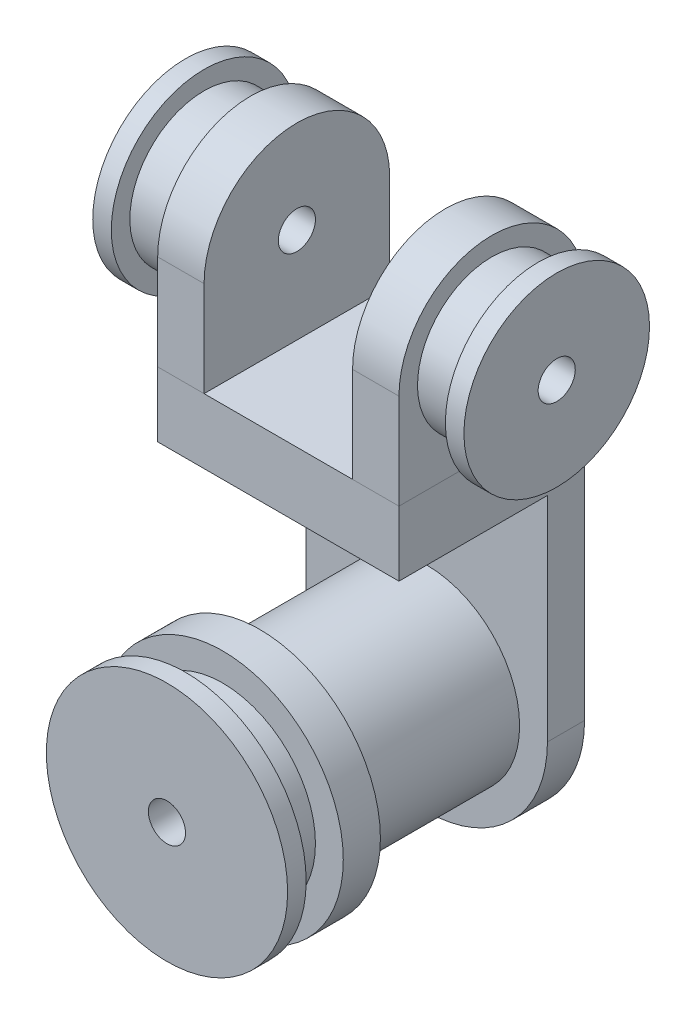
SolidWorks part; units mm, degrees
ref_plane "Front Plane" through (0, 0, 0) normal (0, 0, 1) x (1, 0, 0)
ref_plane "Top Plane" through (0, 0, 0) normal (0, 1, 0) x (1, 0, 0)
ref_plane "Right Plane" through (0, 0, 0) normal (1, 0, 0) x (0, 0, -1)
sketch "Sketch4" plane through (0, 0, 0) normal (0, 0, 1) x (1, 0, 0)
  circle A0 centre (0, 0) radius 1
  circle A1 centre (0, 0) radius 5
  dimension "D1" = 2
  dimension "D2" = 10
extrude "Boss-Extrude5" add sketch "Sketch4" along normal blind 15
ref_plane "Plane2" through (0, 0, 13) normal (0, 0, 1) x (1, 0, 0)
sketch "Sketch5" plane through (0, 0, 15) normal (0, 0, 1) x (1, 0, 0)
  circle A0 centre (0, 0) radius 6.5
  circle A1 centre (0, 0) radius 1 construction
  circle A2 centre (0, 0) radius 1
  dimension "D1" = 13
extrude "Boss-Extrude7" add sketch "Sketch5" against normal blind 2 from surface at -2 starting at plane "Plane2"
sketch "Sketch7" plane through (0, 0, 15) normal (0, 0, 1) x (1, 0, 0)
  circle A0 centre (0, 0) radius 6.5 construction
  circle A1 centre (0, 0) radius 6.5
  circle A2 centre (0, 0) radius 1 construction
  circle A3 centre (0, 0) radius 1
extrude "Boss-Extrude8" add sketch "Sketch7" along normal blind 1
sketch "Sketch8" plane through (0, 0, 0) normal (0, 0, -1) x (-1, 0, 0)
  line L0 (6.5, 0) -> (6.5, 13)
  line L1 (6.5, 13) -> (-6.5, 13)
  line L2 (-6.5, 13) -> (-6.5, 0)
  circle A0 centre (0, 0) radius 6.5 construction
  arc A1 (-6.5, 0) -> (6.5, 0) centre (0, 0) ccw
  circle A2 centre (0, 0) radius 1 construction
  circle A3 centre (0, 0) radius 1
  dimension "D1" = 13
extrude "Boss-Extrude9" add sketch "Sketch8" against normal blind 2
sketch "Sketch9" plane through (0, 0, 0) normal (0, 0, -1) x (-1, 0, 0)
  line L0 (6.5, 0) -> (6.5, 13) construction
  line L3 (-6.5, 13) -> (-6.5, 15)
  line L4 (-6.5, 15) -> (6.5, 15)
  line L5 (6.5, 13) -> (6.5, 15)
  line L6 (-6.5, 13) -> (6.5, 15) construction
  line L7 (-6.5, 15) -> (6.5, 13) construction
  line L8 (-6.5, 13) -> (-6.5, 11.5)
  line L9 (-6.5, 11.5) -> (6.5, 11.5)
  line L10 (6.5, 13) -> (6.5, 11.5)
  line L11 (-6.5, 13) -> (6.5, 11.5) construction
  line L12 (-6.5, 11.5) -> (6.5, 13) construction
  point P5 (0, 14)
  point P8 (0, 12.25)
  dimension "D1" = 2
  dimension "D2" = 1.5
extrude "Boss-Extrude10" add sketch "Sketch9" against normal blind 10
sketch "Sketch10" plane through (6.5, 0, 0) normal (1, 0, 0) x (0, 0, -1)
  line L0 (-5, 20.1326) -> (-5, 15) construction
  line L1 (-10, 15) -> (0, 15) construction
  line L2 (-10, 15) -> (-10, 20.1326)
  line L3 (0, 15) -> (0, 20.1326)
  arc A0 (0, 20.1326) -> (-10, 20.1326) centre (-5, 20.1326) ccw
  circle A1 centre (-5, 20.1326) radius 1
  dimension "D1" = 2
extrude "Boss-Extrude11" add sketch "Sketch10" against normal blind 2.5 separate body
sketch "Sketch11" plane through (6.5, 0, 0) normal (1, 0, 0) x (0, 0, -1)
  circle A0 centre (-5, 20.1326) radius 1
  circle A1 centre (-5, 20.1326) radius 4
  arc A2 (0, 20.1326) -> (-10, 20.1326) centre (-5, 20.1326) ccw construction
  dimension "D1" = 1
extrude "Boss-Extrude12" add sketch "Sketch11" along normal blind 2.5
sketch "Sketch12" plane through (9, 0, 0) normal (1, 0, 0) x (0, 0, -1)
  circle A0 centre (-5, 20.1326) radius 1
  circle A1 centre (-5, 20.1326) radius 5
extrude "Boss-Extrude13" add sketch "Sketch12" along normal blind 1
ref_plane "Plane3" through (0, 0, 0) normal (1, 0, 0) x (0, 0, -1)
mirror "Mirror4" about plane through (0, 0, 0) normal (1, 0, 0) of bodies 116
